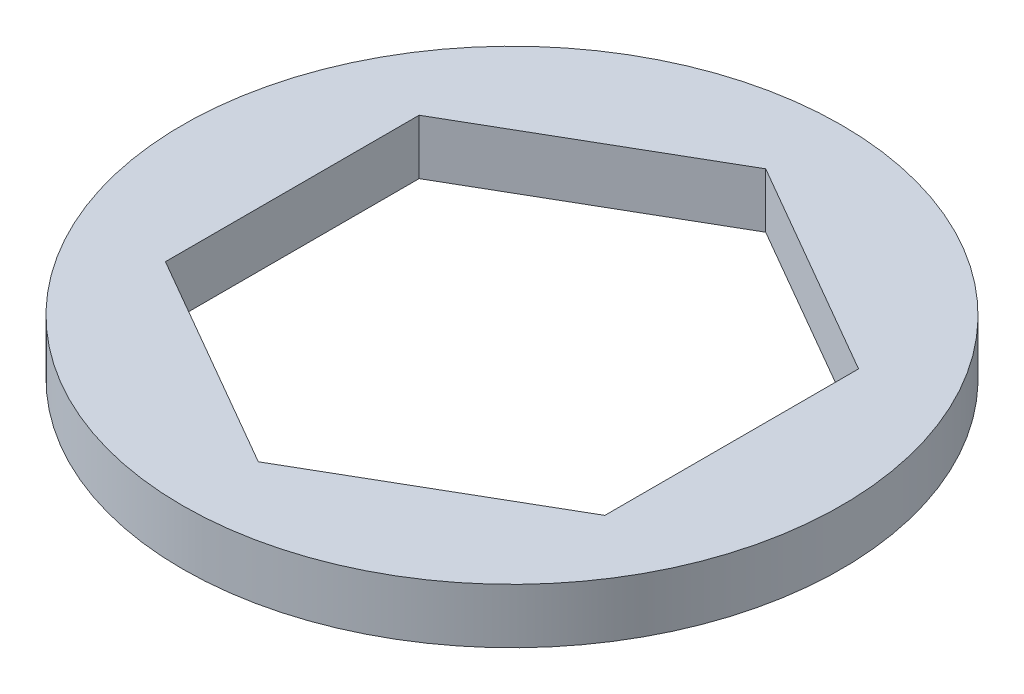
SolidWorks part; units mm, degrees
material "PET"
ref_plane "Front Plane" through (0, 0, 0) normal (0, 0, 1) x (1, 0, 0)
ref_plane "Top Plane" through (0, 0, 0) normal (0, 1, 0) x (1, 0, 0)
ref_plane "Right Plane" through (0, 0, 0) normal (1, 0, 0) x (0, 0, -1)
sketch "Sketch1" plane through (0, 0, 0) normal (0, 1, 0) x (1, 0, 0)
  line L1 (6.35, 3.6662) -> (0, 7.3323)
  line L2 (0, 7.3323) -> (-6.35, 3.6662)
  line L3 (-6.35, 3.6662) -> (-6.35, -3.6662)
  line L4 (-6.35, -3.6662) -> (0, -7.3323)
  line L5 (0, -7.3323) -> (6.35, -3.6662)
  line L6 (6.35, -3.6662) -> (6.35, 3.6662)
  circle A0 centre (0, 0) radius 9.525
  circle A2 centre (0, 0) radius 6.35 construction
  dimension "D1" = 12.7
  dimension "D2" = 19.05
extrude "Boss-Extrude1" add sketch "Sketch1" along normal blind 1.5875
